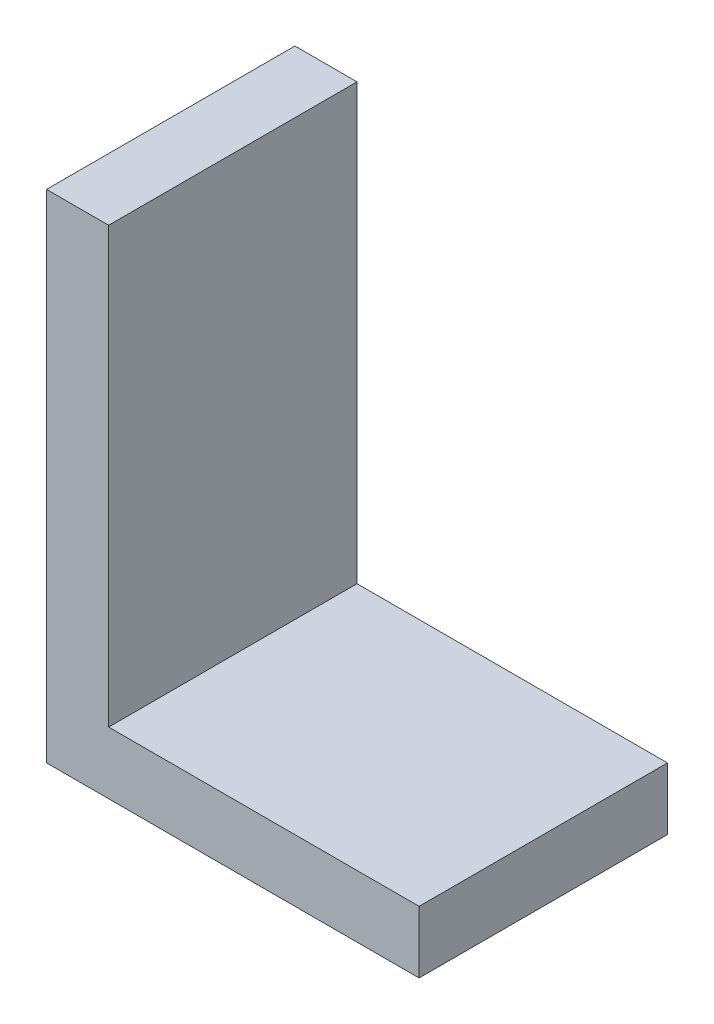
SolidWorks part; units mm, degrees
ref_plane "Front Plane" through (0, 0, 0) normal (0, 0, 1) x (1, 0, 0)
ref_plane "Top Plane" through (0, 0, 0) normal (0, 1, 0) x (1, 0, 0)
ref_plane "Right Plane" through (0, 0, 0) normal (1, 0, 0) x (0, 0, -1)
sketch "Sketch2" plane through (0, 0, 0) normal (0, 0, 1) x (1, 0, 0)
  line L0 (0, 0) -> (0, 40)
  line L1 (0, 40) -> (5, 40)
  line L2 (5, 40) -> (5, 5)
  line L3 (5, 5) -> (30, 5)
  line L4 (30, 5) -> (30, 0)
  line L5 (30, 0) -> (0, 0)
  dimension "D1" = 40
  dimension "D2" = 5
  dimension "D3" = 30
extrude "Boss-Extrude1" add sketch "Sketch2" against normal blind 20
